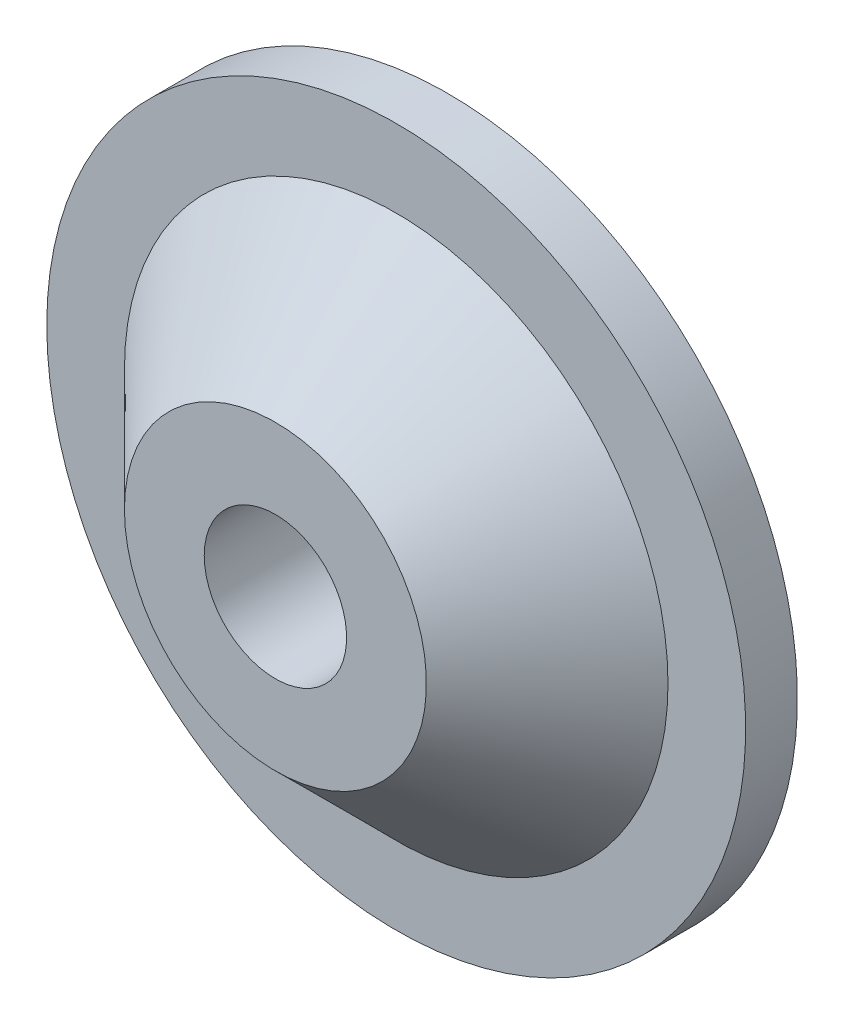
SolidWorks part; units mm, degrees
material "ABS"
ref_plane "Front Plane" through (0, 0, 0) normal (0, 0, 1) x (1, 0, 0)
ref_plane "Top Plane" through (0, 0, 0) normal (0, 1, 0) x (1, 0, 0)
ref_plane "Right Plane" through (0, 0, 0) normal (1, 0, 0) x (0, 0, -1)
sketch "Sketch3" plane through (0, 0, 0) normal (0, 1, 0) x (1, 0, 0)
  line L0 (0, 35.5801) -> (0, 0)
  line L1 (6.3, 0) -> (8.1, 0)
  line L2 (8.1, 0) -> (8.1, 1.2)
  line L3 (8.1, 1.2) -> (1.65, 1.2)
  line L4 (1.65, 1.2) -> (1.65, 0)
  line L6 (3.5, -2.8) -> (-3.5, -2.8) construction
  line L7 (1.65, 0) -> (1.65, -2.8)
  line L8 (1.65, -2.8) -> (3.5, -2.8)
  line L9 (3.5, -2.8) -> (6.3, 0)
  dimension "D1" = 8.1
  dimension "D2" = 1.65
  dimension "D3" = 1.2
revolve "Revolve1" add sketch "Sketch3" angle 360 about L0
chamfer "Chamfer1" distance 0.5 angle 45 1 edges at (-1.65, 0, -1.2)
equation "\"`6.4\"=107.223"
